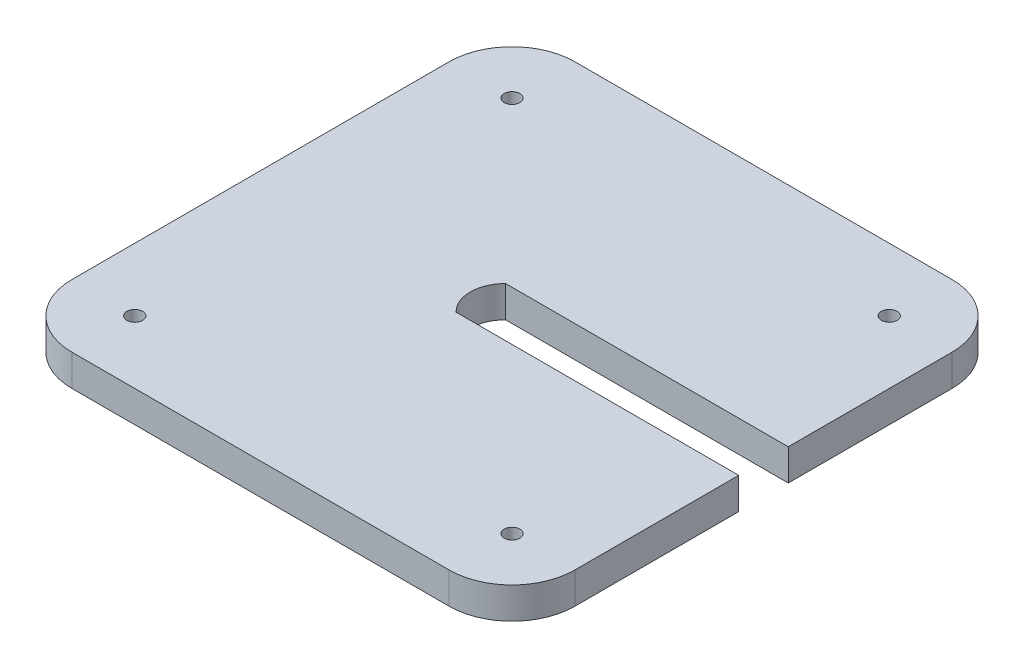
SolidWorks part; units mm, degrees
material "6061 Alloy"
ref_plane "Front Plane" through (0, 0, 0) normal (0, 0, 1) x (1, 0, 0)
ref_plane "Top Plane" through (0, 0, 0) normal (0, 1, 0) x (1, 0, 0)
ref_plane "Right Plane" through (0, 0, 0) normal (1, 0, 0) x (0, 0, -1)
sketch "Sketch1" plane through (0, 0, 0) normal (0, 1, 0) x (1, 0, 0)
  line L0 (63.4519, -36.3407) -> (63.4519, -3.2445)
  line L1 (-38.1481, -3.2445) -> (-38.1481, -79.4445)
  line L2 (-25.4481, -92.1445) -> (50.7519, -92.1445)
  line L3 (63.4519, -79.4445) -> (63.4519, -46.3483)
  line L4 (18.2463, -36.3407) -> (63.4519, -36.3407)
  line L5 (18.2463, -46.3483) -> (63.4519, -46.3483)
  line L6 (-25.4481, 9.4555) -> (50.7519, 9.4555)
  line L7 (18.2463, -46.3483) -> (6.3581, -46.3483)
  line L8 (18.2463, -36.3407) -> (6.3581, -36.3407)
  circle A0 centre (-25.4481, -79.4445) radius 1.5875
  circle A1 centre (50.7519, -79.4445) radius 1.5875
  circle A2 centre (50.7519, -3.2445) radius 1.5875
  circle A3 centre (-25.4481, -3.2445) radius 1.5875
  arc A4 (63.4519, -3.2445) -> (50.7519, 9.4555) centre (50.7519, -3.2445) ccw
  arc A5 (-25.4481, 9.4555) -> (-38.1481, -3.2445) centre (-25.4481, -3.2445) ccw
  arc A6 (-38.1481, -79.4445) -> (-25.4481, -92.1445) centre (-25.4481, -79.4445) ccw
  arc A7 (50.7519, -92.1445) -> (63.4519, -79.4445) centre (50.7519, -79.4445) ccw
  arc A8 (6.3581, -36.3407) -> (6.3581, -46.3483) centre (11.2532, -41.3445) ccw
extrude "Boss-Extrude1" add sketch "Sketch1" along normal blind 6.35
